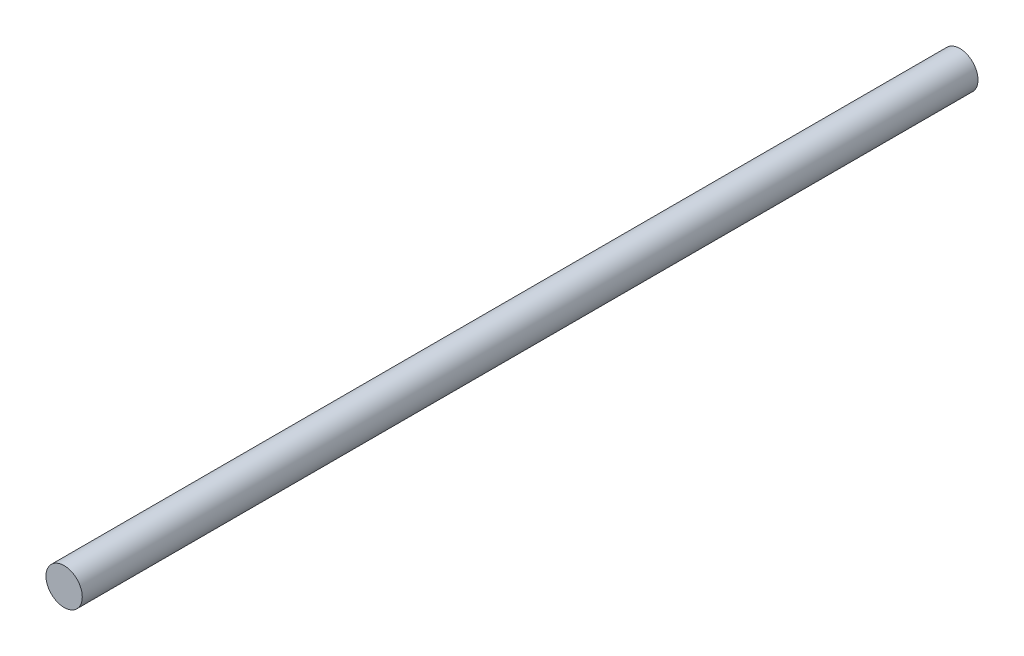
SolidWorks part; units mm, degrees
ref_plane "정면" through (0, 0, 0) normal (0, 0, 1) x (1, 0, 0)
ref_plane "윗면" through (0, 0, 0) normal (0, 1, 0) x (1, 0, 0)
ref_plane "우측면" through (0, 0, 0) normal (1, 0, 0) x (0, 0, -1)
sketch "스케치1" plane through (0, 0, 0) normal (0, 0, 1) x (1, 0, 0)
  circle A0 centre (0, 0) radius 1.5
extrude "돌출1" add sketch "스케치1" along normal blind 74
